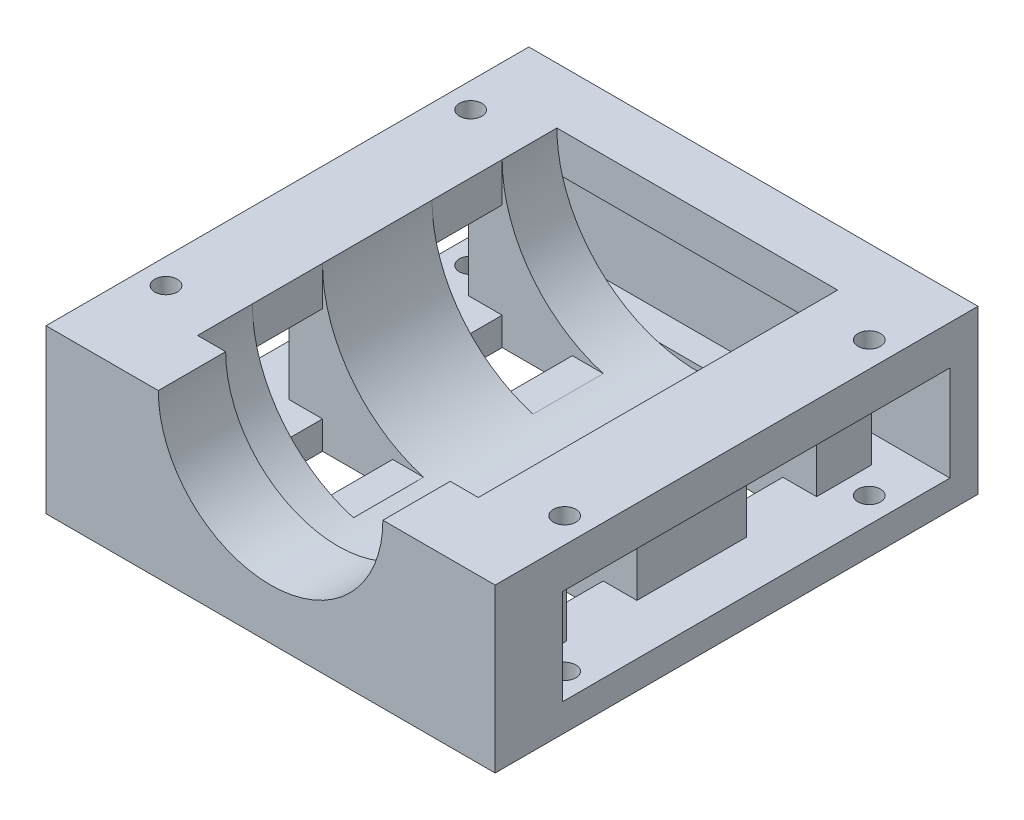
SolidWorks part; units mm, degrees
ref_plane "Front Plane" through (0, 0, 0) normal (0, 0, 1) x (1, 0, 0)
ref_plane "Top Plane" through (0, 0, 0) normal (0, 1, 0) x (1, 0, 0)
ref_plane "Right Plane" through (0, 0, 0) normal (1, 0, 0) x (0, 0, -1)
sketch "Sketch1" plane through (0, 0, 0) normal (0, 0, 1) x (1, 0, 0)
  line L0 (0, 0) -> (80, 0)
  line L1 (80, 0) -> (80, 5)
  line L2 (80, 5) -> (71, 5)
  line L3 (71, 5) -> (71, 22)
  line L4 (80, 29) -> (65, 29)
  line L7 (15, 29) -> (0, 29)
  line L8 (9, 22) -> (9, 5)
  line L9 (9, 5) -> (0, 5)
  line L10 (0, 5) -> (0, 0)
  line L12 (0, 29) -> (0, 22)
  line L13 (0, 22) -> (9, 22)
  line L14 (80, 29) -> (80, 22)
  line L15 (80, 22) -> (71, 22)
  arc A0 (15, 29) -> (65, 29) centre (40, 29) ccw
  dimension "D1" = 50
  dimension "D2" = 9
  dimension "D3" = 5
  dimension "D4" = 7
  dimension "D5" = 15
  dimension "D6" = 17
extrude "Boss-Extrude1" add sketch "Sketch1" along normal blind 64
ref_plane "Plane1" through (0, 0, 64) normal (0, 0, 1) x (1, 0, 0)
sketch "Sketch2" plane through (0, 0, 64) normal (0, 0, 1) x (1, 0, 0)
  line L0 (60, 29) -> (80, 29)
  line L1 (0, 0) -> (80, 0)
  line L2 (0, 0) -> (0, 29)
  line L3 (0, 29) -> (20, 29)
  line L4 (80, 0) -> (80, 29)
  line L5 (40, 0) -> (40, 29) construction
  arc A0 (20, 29) -> (60, 29) centre (40, 29) ccw
  dimension "D1" = 40
extrude "Boss-Extrude2" add sketch "Sketch2" along normal blind 12
ref_plane "Plane2" through (0, 29, 0) normal (0, 1, 0) x (1, 0, 0)
sketch "Sketch3" plane through (0, 29, 0) normal (0, 1, 0) x (1, 0, 0)
  line L0 (15, -64) -> (15, 0) construction
  line L1 (15, -9.75) -> (27.5, -9.75)
  line L2 (15, -9.75) -> (15, -22.25)
  line L3 (15, -22.25) -> (27.5, -22.25)
  line L4 (27.5, -9.75) -> (27.5, -22.25)
  line L5 (40, 0) -> (40, -64) construction
  line L6 (65, 0) -> (15, 0) construction
  line L7 (-55, -64) -> (55, -64) construction
  line L8 (40, -32) -> (15, -32) construction
  line L9 (15, 0) -> (65, -64) construction
  line L10 (65, 0) -> (15, -64) construction
  line L11 (15, -32) -> (40, 0) construction
  line L12 (27.5, -16) -> (15, -16) construction
  line L13 (65, -64) -> (65, 0) construction
  line L14 (65, -64) -> (60, -64) construction
  line L15 (65, -22.25) -> (52.5, -22.25)
  line L16 (52.5, -9.75) -> (52.5, -22.25)
  line L17 (65, -9.75) -> (52.5, -9.75)
  line L18 (65, -9.75) -> (65, -22.25)
  line L19 (15, -41.75) -> (27.5, -41.75)
  line L20 (27.5, -54.25) -> (27.5, -41.75)
  line L21 (15, -54.25) -> (27.5, -54.25)
  line L22 (15, -54.25) -> (15, -41.75)
  line L23 (65, -54.25) -> (65, -41.75)
  line L24 (65, -54.25) -> (52.5, -54.25)
  line L25 (52.5, -54.25) -> (52.5, -41.75)
  line L26 (65, -41.75) -> (52.5, -41.75)
  point P23 (15, -16)
extrude "Cut-Extrude1" cut sketch "Sketch3" against normal up to surface (29 mm away) up to face at (40, 0, 38)
ref_plane "Plane3" through (15, 0, 0) normal (1, 0, 0) x (0, 0, -1)
sketch "Sketch5" plane through (15, 0, 0) normal (1, 0, 0) x (0, 0, -1)
  line L0 (-54.25, 0) -> (-54.25, 29) construction
  line L1 (-54.25, 22) -> (-41.75, 22)
  line L2 (-54.25, 22) -> (-54.25, 5)
  line L3 (-54.25, 5) -> (-41.75, 5)
  line L4 (-41.75, 22) -> (-41.75, 5)
  line L5 (-41.75, 0) -> (-41.75, 29) construction
  line L8 (-54.25, 22) -> (-54.25, 29) construction
  line L9 (-54.25, 0) -> (-54.25, 5) construction
  line L16 (-22.25, 22) -> (-9.75, 22)
  line L17 (-22.25, 22) -> (-22.25, 5)
  line L18 (-22.25, 5) -> (-9.75, 5)
  line L19 (-9.75, 22) -> (-9.75, 5)
  line L20 (-22.25, 0) -> (-22.25, 7.3494) construction
  line L21 (-9.75, 0) -> (-9.75, 29) construction
  dimension "D1" = 7
  dimension "D2" = 5
extrude "Cut-Extrude2" cut sketch "Sketch5" against normal up to surface and the other way up to surface up to face at (9, 13.5, 32) other way up to face at (71, 13.5, 32)
ref_plane "Plane4" through (0, 0, 0) normal (0, -1, 0) x (-1, 0, 0)
sketch "Sketch6" plane through (0, 0, 0) normal (0, -1, 0) x (-1, 0, 0)
  line L0 (-4.8728, -32) -> (0, -32) construction
  line L1 (-15, 0) -> (-15, -76) construction
  line L2 (-15, 15.95) -> (-15, -15.95) construction
  line L3 (0, -76) -> (-80, -76) construction
  line L4 (-15, -54.25) -> (0, -64) construction
  line L5 (-27.5, -54.25) -> (-15, -54.25) construction
  line L7 (0, -76) -> (0, 0) construction
  line L9 (0, 0) -> (-80, 0) construction
  line L10 (-40, -76) -> (-40, 0) construction
  line L11 (0, -64) -> (-15, -64) construction
  line L12 (-55, -64) -> (55, -64) construction
  line L13 (0, -64) -> (-15, 0) construction
  line L14 (0, -64) -> (-8.9998, -64) construction
  line L15 (-8.9998, -64) -> (-8.9998, -54.25) construction
  line L16 (-8.9998, -54.25) -> (0, -54.25) construction
  line L17 (0, -54.25) -> (-8.9998, -64) construction
  line L18 (0, -64) -> (-8.9998, -54.25) construction
  circle A0 centre (-4.4999, -59.125) radius 2
  circle A1 centre (-4.4999, -4.875) radius 2
  circle A2 centre (-75.5001, -4.875) radius 2
  circle A3 centre (-75.5001, -59.125) radius 2
  point P13 (-4.4999, -59.125)
  dimension "D1" = 4
extrude "Cut-Extrude3" cut sketch "Sketch6" against normal up to surface (29 mm away) up to face at (67, 29, 40.8)
ref_plane "Plane5" through (0, 0, 0) normal (0, 0, -1) x (-1, 0, 0)
sketch "Sketch7" plane through (0, 0, 0) normal (0, 0, -1) x (-1, 0, 0)
  line L1 (-80, 0) -> (0, 0)
  line L2 (-80, 0) -> (-80, 29)
  line L3 (-80, 29) -> (0, 29)
  line L4 (0, 0) -> (0, 29)
extrude "Boss-Extrude3" add sketch "Sketch7" along normal blind 10
ref_plane "Plane6" through (80, 0, 0) normal (1, 0, 0) x (0, 0, -1)
sketch "Sketch8" plane through (80, 0, 0) normal (1, 0, 0) x (0, 0, -1)
  line L0 (0, 5) -> (10, 5) construction
  line L1 (0, 22) -> (5, 22)
  line L2 (0, 22) -> (0, 5)
  line L3 (0, 5) -> (5, 5)
  line L4 (5, 22) -> (5, 5)
  line L5 (10, 29) -> (10, 0) construction
  line L6 (0, 22) -> (10, 5) construction
  line L8 (0, 5) -> (10, 22) construction
  point P2 (5, 13.5)
  point P11 (0.2154, 5.3662)
  point P12 (5, 13.5)
extrude "Cut-Extrude4" cut sketch "Sketch8" against normal up to surface (80 mm away) up to face at (0, 14.5, 33)
